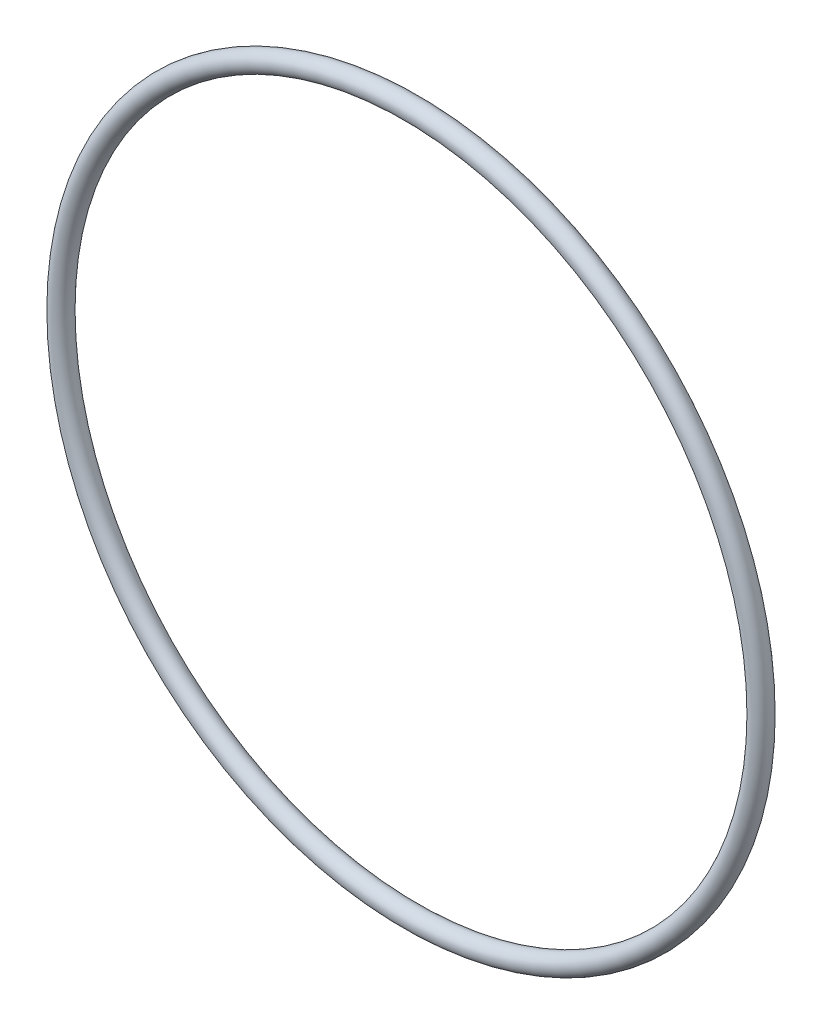
SolidWorks part; units mm, degrees
ref_plane "Front" through (0, 0, 0) normal (0, 0, 1) x (1, 0, 0)
ref_plane "Top" through (0, 0, 0) normal (0, 1, 0) x (1, 0, 0)
ref_plane "Right" through (0, 0, 0) normal (1, 0, 0) x (0, 0, -1)
sketch "Sketch1" plane through (0, 0, 0) normal (1, 0, 0) x (0, -1, 0)
  line L0 (0, -1.7653) -> (0, 1.7653) construction
  line L2 (-70.0176, 0) -> (70.0176, 0) construction
  line L3 (-60.1218, 0) -> (60.1218, 0) construction
  circle A0 centre (61.8871, 0) radius 1.7653
  point P9 (60.1218, 0)
  point P10 (63.6524, 0)
  point P13 (61.8871, 1.7653)
  point P14 (61.8871, -1.7653)
  dimension "Width" = 3.5306
  dimension "ID" = 120.2436
revolve "Revolve1" add sketch "Sketch1" angle 360 about L0
